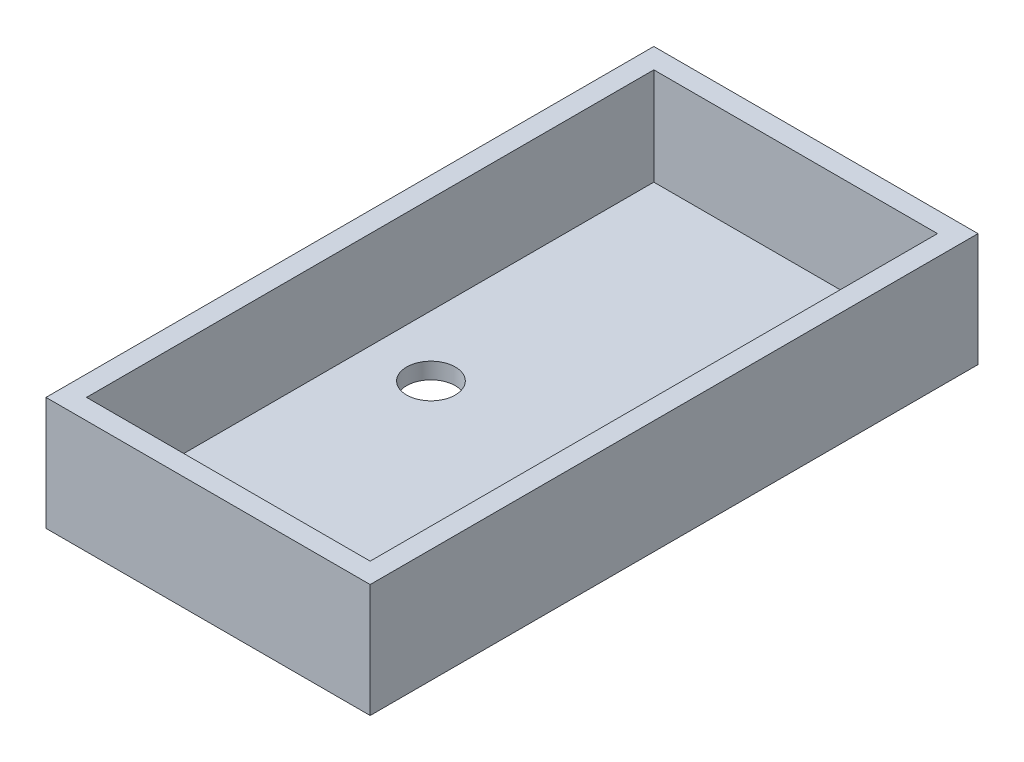
SolidWorks part; units mm, degrees
material "ABS"
ref_plane "Front Plane" through (0, 0, 0) normal (0, 0, 1) x (1, 0, 0)
ref_plane "Top Plane" through (0, 0, 0) normal (0, 1, 0) x (1, 0, 0)
ref_plane "Right Plane" through (0, 0, 0) normal (1, 0, 0) x (0, 0, -1)
sketch "Sketch1" plane through (0, 0, 0) normal (0, 1, 0) x (1, 0, 0)
  line L0 (0, 44.2221) -> (0, -60.5363) construction
  line L1 (-20, 37.5) -> (20, 37.5)
  line L2 (-20, 37.5) -> (-20, -37.5)
  line L3 (-20, -37.5) -> (20, -37.5)
  line L4 (20, 37.5) -> (20, -37.5)
  line L5 (-20, 37.5) -> (20, -37.5) construction
  line L6 (-20, -37.5) -> (20, 37.5) construction
  circle A0 centre (-10, 0) radius 1.5
  circle A1 centre (10, 0) radius 1.5
  point P0 (0, 0)
  dimension "D4" = 3
  dimension "D1" = 75
  dimension "D2" = 40
  dimension "D3" = 20
extrude "Boss-Extrude1" add sketch "Sketch1" along normal blind 14
sketch "Sketch2" plane through (0, 14, 0) normal (0, 1, 0) x (1, 0, 0)
  line L0 (-20, 37.5) -> (-20, -37.5) construction
  line L1 (-17.5, 35) -> (17.5, 35)
  line L2 (-17.5, 35) -> (-17.5, -35)
  line L3 (-17.5, -35) -> (17.5, -35)
  line L4 (17.5, 35) -> (17.5, -35)
  line L5 (-17.5, 35) -> (17.5, -35) construction
  line L6 (-17.5, -35) -> (17.5, 35) construction
  line L7 (-20, -37.5) -> (20, -37.5) construction
  point P0 (0, 0)
  dimension "D1" = 2.5
  dimension "D2" = 2.5
extrude "Cut-Extrude1" cut sketch "Sketch2" against normal blind 12
sketch "Sketch3" plane through (0, 2, 0) normal (0, 1, 0) x (1, 0, 0)
  circle A0 centre (-10, 0) radius 3
  circle A1 centre (10, 0) radius 3
  dimension "D1" = 6
extrude "Cut-Extrude2" cut sketch "Sketch3" against normal blind 2
